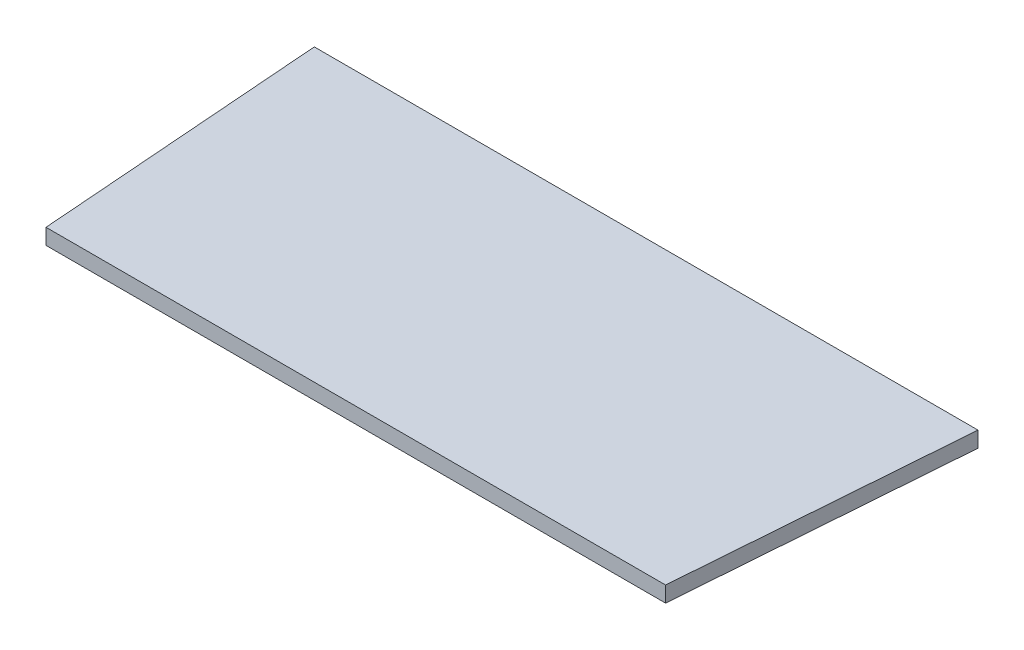
SolidWorks part; units mm, degrees
material "Стекло кварцевое прозрачное"
ref_plane "Спереди" through (0, 0, 0) normal (0, 0, 1) x (1, 0, 0)
ref_plane "Сверху" through (0, 0, 0) normal (0, 1, 0) x (1, 0, 0)
ref_plane "Справа" through (0, 0, 0) normal (1, 0, 0) x (0, 0, -1)
sketch "Эскиз1" plane through (0, 0, 0) normal (0, 1, 0) x (1, 0, 0)
  line L0 (-1120, 490) -> (1120, 490)
  line L1 (1120, 490) -> (1045.5, -490)
  line L2 (1045.5, -490) -> (-1045.5, -490)
  line L3 (-1045.5, -490) -> (-1120, 490)
  line L4 (0, 774.4) -> (0, -774.4) construction
  line L5 (-1082.75, 0) -> (1082.75, 0) construction
  dimension "D1" = 2240
  dimension "D2" = 980
  dimension "D3" = 2091
extrude "Бобышка-Вытянуть1" add sketch "Эскиз1" along normal mid plane 53
